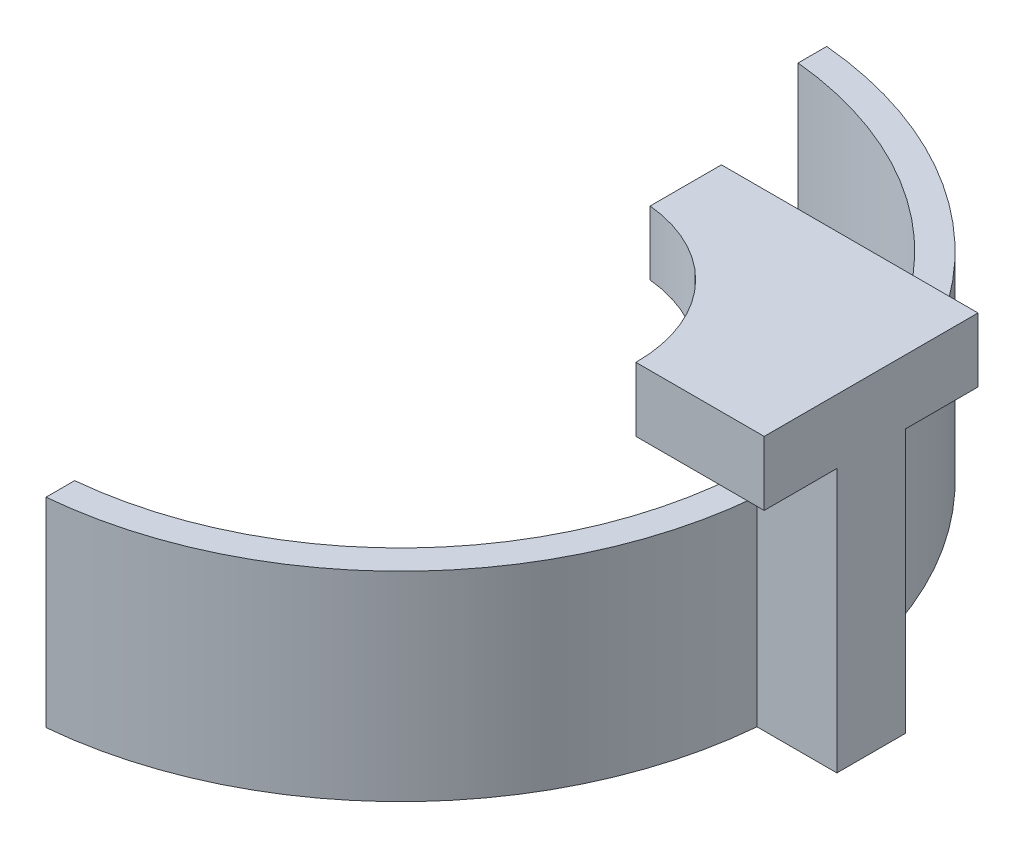
SolidWorks part; units mm, degrees
ref_plane "Front Plane" through (0, 0, 0) normal (0, 0, 1) x (1, 0, 0)
ref_plane "Top Plane" through (0, 0, 0) normal (0, 1, 0) x (1, 0, 0)
ref_plane "Right Plane" through (0, 0, 0) normal (1, 0, 0) x (0, 0, -1)
sketch "Sketch1" plane through (0, 0, 0) normal (0, 1, 0) x (1, 0, 0)
  line L4 (2.5, 27.3861) -> (2.5, 25.3772)
  line L6 (-2.5, 0) -> (2.5, 0) construction
  line L7 (2.5, -25.3772) -> (2.5, -27.3861)
  arc A2 (2.5, -27.3861) -> (2.5, 27.3861) centre (0, 0) ccw
  arc A5 (2.5, -25.3772) -> (2.5, 25.3772) centre (0, 0) ccw
  point P4 (24.3858, 7.4555)
  point P12 (26.2984, 8.0402)
extrude "Boss-Extrude1" add sketch "Sketch1" along normal blind 12
sketch "Sketch2" plane through (0, 0, 0) normal (0, 1, 0) x (1, 0, 0)
  line L0 (2.5, 27.3861) -> (1.8636, 20.4151)
  line L1 (2.5, -27.3861) -> (1.8636, -20.4151)
  arc A0 (2.5, 27.3861) -> (2.5, -27.3861) centre (0, 0) cw
  arc A1 (1.8636, 20.4151) -> (1.8636, -20.4151) centre (0, 0) cw
  dimension "D1" = 7
extrude "Boss-Extrude2" add sketch "Sketch2" against normal blind 2
sketch "Sketch4" plane through (0, -2, 0) normal (0, 1, 0) x (1, 0, 0)
  line L1 (27, 2.4) -> (33, 2.4)
  line L2 (27, 2.4) -> (27, -2.4)
  line L3 (27, -2.4) -> (33, -2.4)
  line L4 (33, 2.4) -> (33, -2.4)
  line L5 (30, -2.4) -> (30, 2.4) construction
  line L6 (27, 0) -> (33, 0) construction
  point P0 (30, 0)
  dimension "D1" = 6
  dimension "D2" = 4.8
  dimension "D3" = 30
extrude "Boss-Extrude3" add sketch "Sketch4" along normal blind 20
sketch "Sketch5" plane through (0, 18, 0) normal (0, 1, 0) x (1, 0, 0)
  line L0 (33, -2.4) -> (33, 2.4) construction
  line L4 (33, 7.5) -> (33, -7.5)
  line L6 (30, 0) -> (33, 0) construction
  line L7 (33, 7.5) -> (15, 7.5)
  line L8 (15, 7.5) -> (15, -7.5)
  line L9 (15, -7.5) -> (33, -7.5)
  point P0 (30, 0)
  dimension "D1" = 3
  dimension "D2" = 18
  dimension "D3" = 15
extrude "Boss-Extrude4" add sketch "Sketch5" along normal blind 3 and the other way blind 1.5
ref_plane "Plane1" through (0, 16.5, 0) normal (0, -1, 0) x (-1, 0, 0)
sketch "Sketch6" plane through (0, 21, 0) normal (0, 1, 0) x (1, 0, 0)
  line L0 (24, -7.5) -> (15, -7.5)
  line L1 (15, 7.5) -> (15, -7.5) construction
  line L2 (15, -7.5) -> (33, -7.5) construction
  line L3 (15, -7.5) -> (15, 2.5)
  arc A0 (24, -7.5) -> (15, 2.5) centre (14.0001, -7.4499) ccw
  dimension "D2" = 10
  dimension "D1" = 9
  dimension "D3" = 5
extrude "Cut-Extrude1" cut sketch "Sketch6" against normal blind 5
ref_plane "Plane2" through (27, 0, 0) normal (-1, 0, 0) x (0, 0, 1)
ref_plane "Plane3" through (0, 0, 2.4) normal (0, 0, 1) x (1, 0, 0)
ref_plane "Plane4" through (0, 0, -2.4) normal (0, 0, -1) x (-1, 0, 0)
